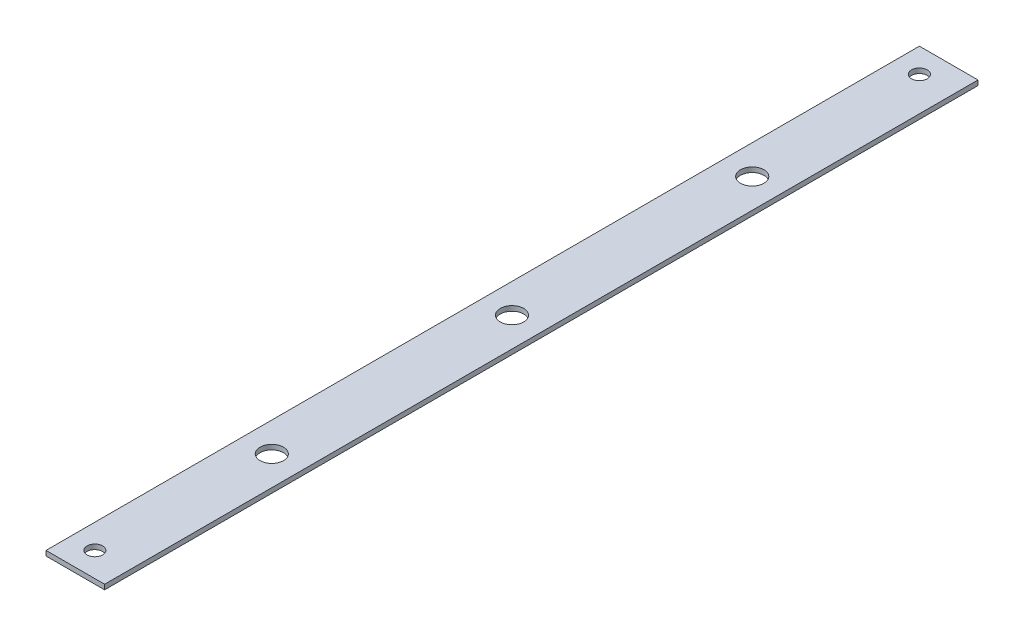
SolidWorks part; units mm, degrees
ref_plane "Front Plane" through (0, 0, 0) normal (0, 0, 1) x (1, 0, 0)
ref_plane "Top Plane" through (0, 0, 0) normal (0, 1, 0) x (1, 0, 0)
ref_plane "Right Plane" through (0, 0, 0) normal (1, 0, 0) x (0, 0, -1)
sketch "Sketch1" plane through (0, 0, 0) normal (0, 0, 1) x (1, 0, 0)
  line L0 (0, 0) -> (0, 2.5)
  line L3 (0, 2.5) -> (30, 2.5)
  line L4 (30, 2.5) -> (30, 0)
  line L5 (30, 0) -> (0, 0)
  dimension "D2" = 2.5
  dimension "D4" = 30
extrude "Boss-Extrude1" add sketch "Sketch1" along normal mid plane 447.2
sketch "Sketch2" plane through (0, 2.5, 0) normal (0, 1, 0) x (1, 0, 0)
  line L0 (-142.3856, 0) -> (299.1222, 0) construction
  line L1 (30, 223.6) -> (0, 223.6) construction
  line L2 (30, -223.6) -> (30, 223.6) construction
  line L4 (30, -223.6) -> (0, -223.6) construction
  line L5 (0, -223.6) -> (0, 223.6) construction
  circle A0 centre (12.5, 211.1) radius 4
  circle A1 centre (12.5, -211.1) radius 4
  circle A2 centre (15, -123) radius 6
  circle A3 centre (15, 123) radius 6
  circle A4 centre (15, 0) radius 6
  dimension "D2" = 8
  dimension "D6" = 223.6
  dimension "D11" = 12
  dimension "D12" = 12
  dimension "D13" = 12
  dimension "D1" = 12.5
  dimension "D3" = 17.5
  dimension "D4" = 12.5
  dimension "D5" = 223.6
  dimension "D7" = 15
  dimension "D8" = 422.2
  dimension "D9" = 17.5
  dimension "D10" = 123
  dimension "D14" = 15
  dimension "D16" = 123
extrude "Cut-Extrude1" cut sketch "Sketch2" against normal through all
